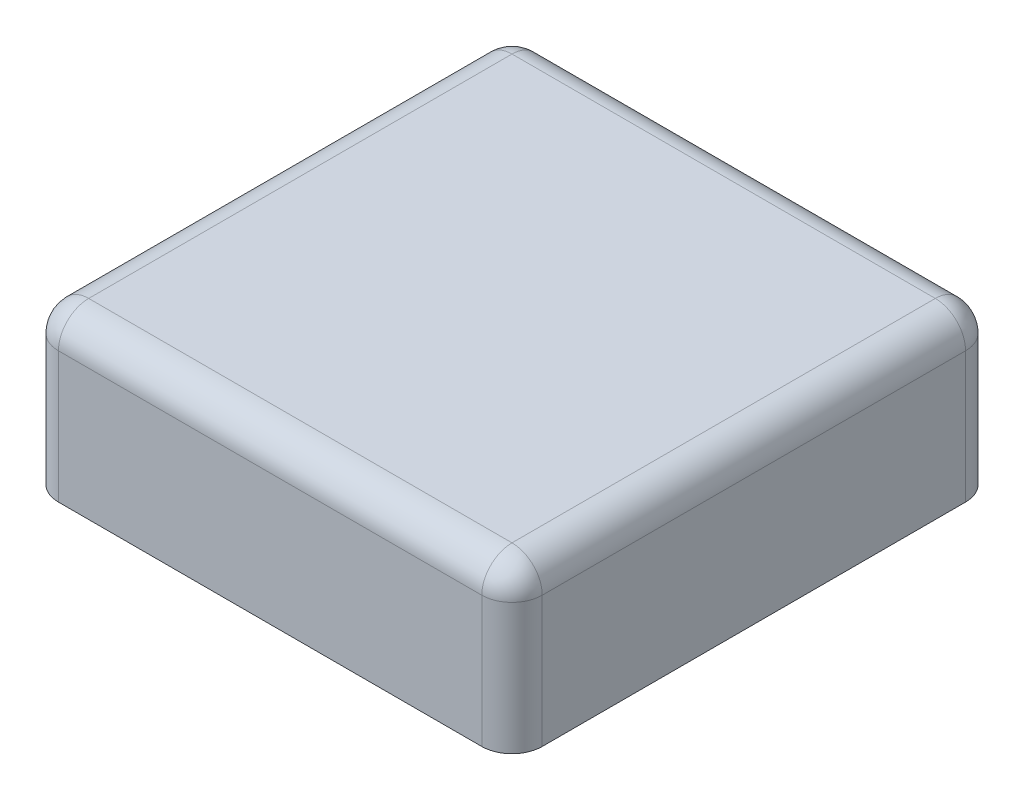
SolidWorks part; units mm, degrees
ref_plane "Front Plane" through (0, 0, 0) normal (0, 0, 1) x (1, 0, 0)
ref_plane "Top Plane" through (0, 0, 0) normal (0, 1, 0) x (1, 0, 0)
ref_plane "Right Plane" through (0, 0, 0) normal (1, 0, 0) x (0, 0, -1)
sketch "Sketch1" plane through (0, 0, 0) normal (0, 1, 0) x (1, 0, 0)
  line L1 (-10.1342, 10.2951) -> (1.8658, 10.2951)
  line L2 (-10.1342, 10.2951) -> (-10.1342, -1.7049)
  line L3 (-10.1342, -1.7049) -> (1.8658, -1.7049)
  line L4 (1.8658, 10.2951) -> (1.8658, -1.7049)
  dimension "D1" = 12
  dimension "D2" = 12
extrude "Boss-Extrude1" add sketch "Sketch1" along normal blind 4
fillet "Fillet1" radius 0.75 8 edges at (-10.1342, 2, 1.7049) (-10.1342, 2, -10.2951) (1.8658, 2, -10.2951) (1.8658, 2, 1.7049) (-4.1342, 4, 1.7049) (1.8658, 4, -4.2951) (-4.1342, 4, -10.2951) (-10.1342, 4, -4.2951)
